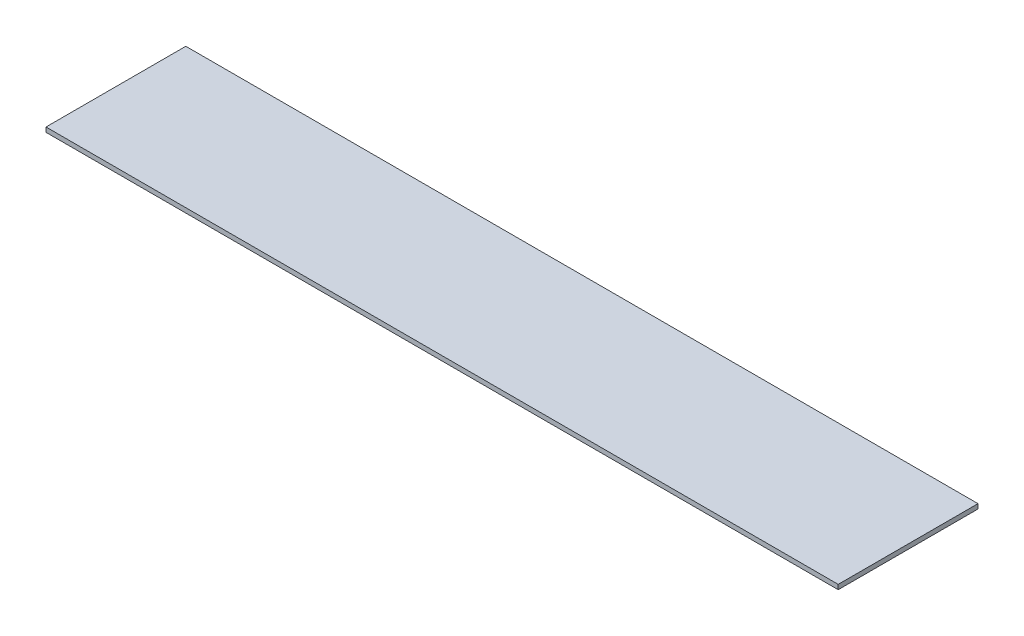
SolidWorks part; units mm, degrees
ref_plane "Front Plane" through (0, 0, 0) normal (0, 0, 1) x (1, 0, 0)
ref_plane "Top Plane" through (0, 0, 0) normal (0, 1, 0) x (1, 0, 0)
ref_plane "Right Plane" through (0, 0, 0) normal (1, 0, 0) x (0, 0, -1)
sketch "Sketch1" plane through (0, 0, 0) normal (0, 1, 0) x (1, 0, 0)
  line L1 (-49.9301, 65.5828) -> (120.0699, 65.5828)
  line L2 (-49.9301, 65.5828) -> (-49.9301, 35.5828)
  line L3 (-49.9301, 35.5828) -> (120.0699, 35.5828)
  line L4 (120.0699, 65.5828) -> (120.0699, 35.5828)
  dimension "D1" = 170
  dimension "D2" = 30
extrude "Boss-Extrude1" add sketch "Sketch1" along normal blind 1
